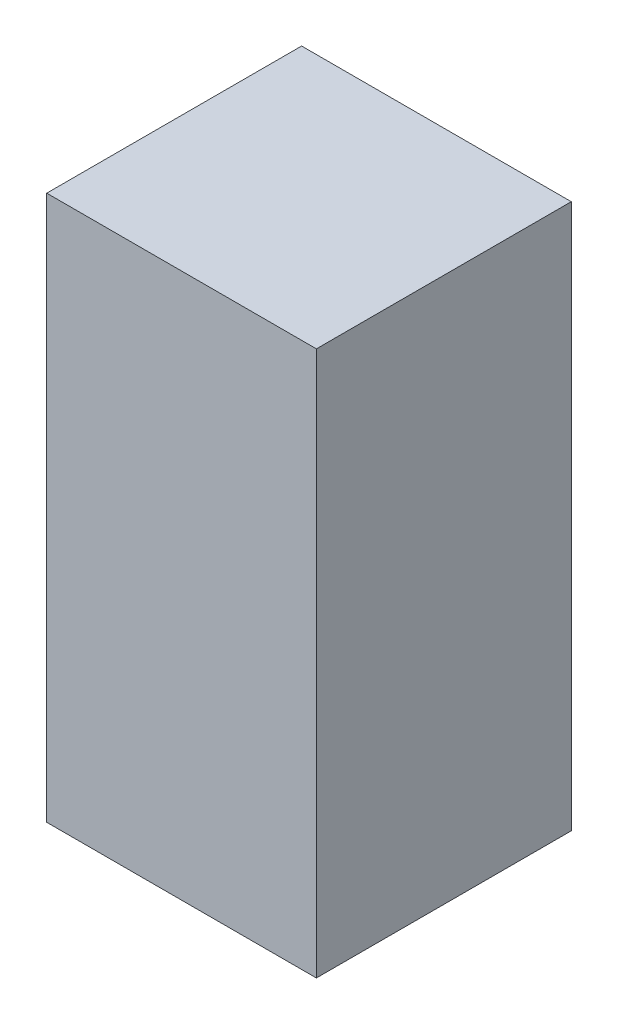
SolidWorks part; units mm, degrees
ref_plane "Front Plane" through (0, 0, 0) normal (0, 0, 1) x (1, 0, 0)
ref_plane "Top Plane" through (0, 0, 0) normal (0, 1, 0) x (1, 0, 0)
ref_plane "Right Plane" through (0, 0, 0) normal (1, 0, 0) x (0, 0, -1)
sketch "Sketch1" plane through (0, 0, 0) normal (0, 1, 0) x (1, 0, 0)
  line L1 (0, 0) -> (37.084, 0)
  line L2 (0, 0) -> (0, 35.052)
  line L3 (0, 35.052) -> (37.084, 35.052)
  line L4 (37.084, 0) -> (37.084, 35.052)
  dimension "D1" = 37.084
  dimension "D2" = 35.052
extrude "Boss-Extrude1" add sketch "Sketch1" along normal blind 74.93
